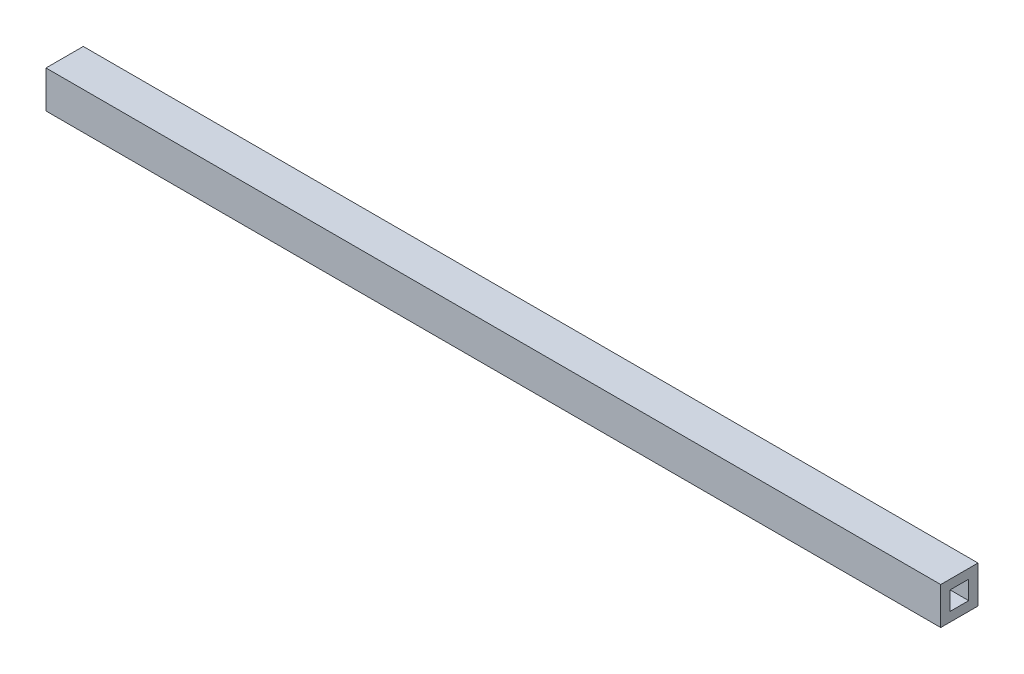
SolidWorks part; units mm, degrees
ref_plane "Front Plane" through (0, 0, 0) normal (0, 0, 1) x (1, 0, 0)
ref_plane "Top Plane" through (0, 0, 0) normal (0, 1, 0) x (1, 0, 0)
ref_plane "Right Plane" through (0, 0, 0) normal (1, 0, 0) x (0, 0, -1)
sketch "Sketch1" plane through (0, 0, 0) normal (0, 0, 1) x (1, 0, 0)
  line L1 (304.8, -12.7) -> (-304.8, -12.7)
  line L2 (304.8, -12.7) -> (304.8, 12.7)
  line L3 (304.8, 12.7) -> (-304.8, 12.7)
  line L4 (-304.8, -12.7) -> (-304.8, 12.7)
  line L5 (304.8, -12.7) -> (-304.8, 12.7) construction
  line L6 (304.8, 12.7) -> (-304.8, -12.7) construction
  point P0 (0, 0)
  point P6 (0, 0)
  dimension "D1" = 609.6
  dimension "D2" = 25.4
extrude "Boss-Extrude1" add sketch "Sketch1" along normal blind 25.4
sketch "Sketch2" plane through (304.8, 0, 0) normal (1, 0, 0) x (0, 0, -1)
  line L1 (-6.3289, -6.35) -> (-19.0711, -6.35)
  line L2 (-6.3289, -6.35) -> (-6.3289, 6.35)
  line L3 (-6.3289, 6.35) -> (-19.0711, 6.35)
  line L4 (-19.0711, -6.35) -> (-19.0711, 6.35)
  line L5 (-6.3289, -6.35) -> (-19.0711, 6.35) construction
  line L6 (-6.3289, 6.35) -> (-19.0711, -6.35) construction
  point P0 (-12.7, 0)
  point P5 (0, 0)
  dimension "D1" = 12.7421
  dimension "D2" = 12.7
extrude "Cut-Extrude1" cut sketch "Sketch2" against normal through all
